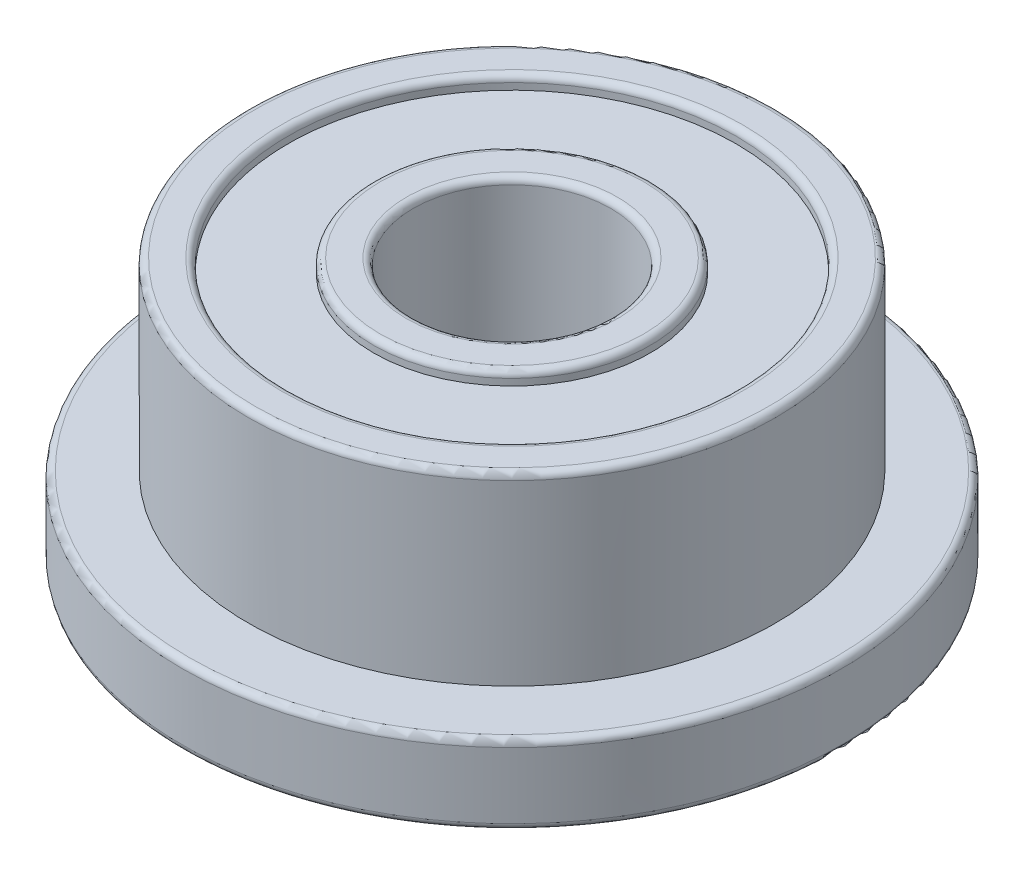
SolidWorks part; units mm, degrees
ref_plane "Front Plane" through (0, 0, 0) normal (0, 0, 1) x (1, 0, 0)
ref_plane "Top Plane" through (0, 0, 0) normal (0, 1, 0) x (1, 0, 0)
ref_plane "Right Plane" through (0, 0, 0) normal (1, 0, 0) x (0, 0, -1)
sketch "Sketch1" plane through (0, 0, 0) normal (0, 0, 1) x (1, 0, 0)
  line L1 (0.75, 1) -> (1.05, 1)
  line L2 (0.75, 1) -> (0.75, -1)
  line L3 (0.75, -1) -> (1.05, -1)
  line L4 (1.05, 1) -> (1.05, -1)
  point P4 (0.75, 0)
  dimension "D1" = 0.75
  dimension "D2" = 0.3
  dimension "D3" = 2
ref_axis "Axis1" through (0, -1.1, 0) along (0, 1, 0)
revolve "Revolve1" add sketch "Sketch1" angle 360 about axis through (0, -1.1, 0) along (0, 1, 0)
sketch "Sketch2" plane through (0, 0, 0) normal (0, 0, 1) x (1, 0, 0)
  line L0 (1.7, 1) -> (1.7, -1)
  line L1 (1.7, -1) -> (2.5, -1)
  line L2 (2.5, -1) -> (2.5, -0.4)
  line L3 (2.5, -0.4) -> (2, -0.4)
  line L4 (2, -0.4) -> (2, 1)
  line L5 (2, 1) -> (1.7, 1)
  line L6 (-1.05, -1) -> (1.05, -1) construction
  line L7 (-1.05, -1) -> (1.05, -1)
  line L8 (1.05, 1) -> (-1.05, 1) construction
  line L9 (1.05, 1) -> (-1.05, 1)
  line L10 (0, -1.1) -> (0, 1.1) construction
  dimension "D1" = 0.6
  dimension "D2" = 2
  dimension "D3" = 2.5
  dimension "D4" = 0.3
revolve "Revolve2" add sketch "Sketch2" angle 360 about axis through (0, -1.1, 0) along (0, 1, 0)
sketch "Sketch3" plane through (0, 0, 0) normal (0, 0, 1) x (1, 0, 0)
  line L0 (1.05, 1) -> (-1.05, 1) construction
  line L1 (1.05, 1) -> (-1.05, 1) construction
  line L2 (1.7, 1) -> (-1.7, 1) construction
  line L3 (1.7, 1) -> (-1.7, 1) construction
  line L4 (-1.05, -1) -> (1.05, -1) construction
  line L5 (-1.05, -1) -> (1.05, -1) construction
  line L6 (-1.7, -1) -> (1.7, -1) construction
  line L7 (-1.7, -1) -> (1.7, -1) construction
  line L8 (1.05, -1) -> (1.05, 1) construction
  line L9 (1.05, 0.9) -> (1.7, 0.9)
  line L10 (1.05, 0.9) -> (1.05, -0.9)
  line L11 (1.05, -0.9) -> (1.7, -0.9)
  line L12 (1.7, 0.9) -> (1.7, -0.9)
  dimension "D1" = 0.1
  dimension "D2" = 0.1
revolve "Revolve3" add sketch "Sketch3" angle 360 about axis through (0, -1.1, 0) along (0, 1, 0)
fillet "Fillet1" radius 0.05 4 edges at (0, -1, -0.75) (0, -1, -1.05) (0, 1, -1.05) (0, 1, -0.75)
fillet "Fillet2" radius 0.05 5 edges at (0, -1, -2.5) (0, -0.4, -2.5) (0, -1, -1.7) (0, 1, -1.7) (0, 1, -2)
